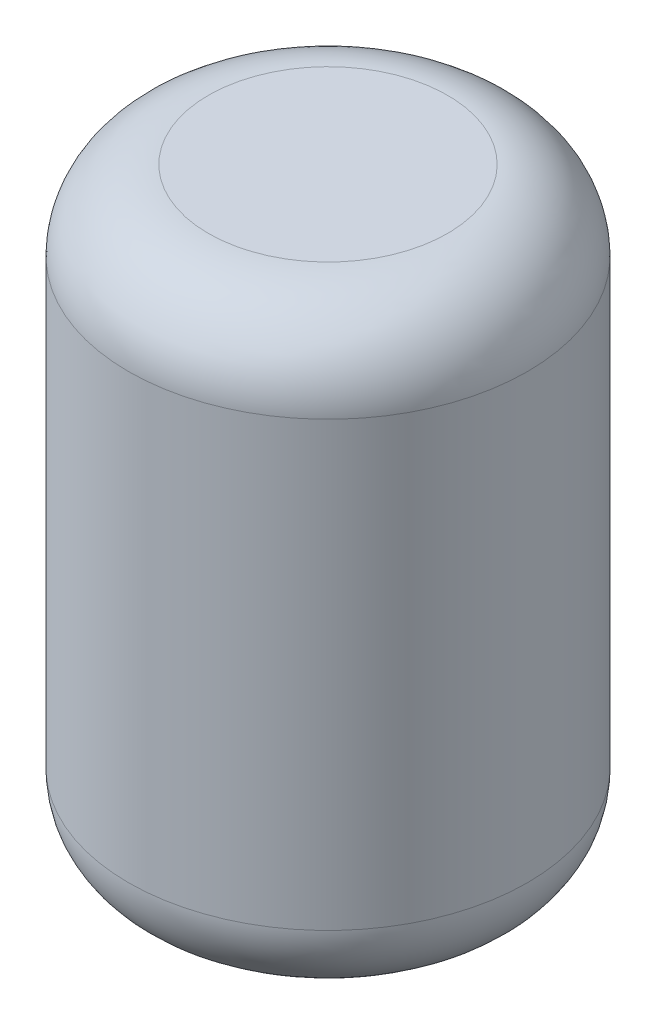
SolidWorks part; units mm, degrees
material "Cast Alloy Steel"
ref_plane "Front Plane" through (0, 0, 0) normal (0, 0, 1) x (1, 0, 0)
ref_plane "Top Plane" through (0, 0, 0) normal (0, 1, 0) x (1, 0, 0)
ref_plane "Right Plane" through (0, 0, 0) normal (1, 0, 0) x (0, 0, -1)
sketch "Sketch1" plane through (0, 0, 0) normal (0, 1, 0) x (1, 0, 0)
  circle A0 centre (0, 0) radius 100
  circle A1 centre (0, 0) radius 98
  dimension "D1" = 200
  dimension "D2" = 2
extrude "Boss-Extrude1" add sketch "Sketch1" along normal blind 300
sketch "Sketch2" plane through (0, 0, 0) normal (0, -1, 0) x (1, 0, 0)
  circle A0 centre (0, 0) radius 100
extrude "Boss-Extrude2" add sketch "Sketch2" against normal blind 2
sketch "Sketch4" plane through (0, 300, 0) normal (0, 1, 0) x (1, 0, 0)
  circle A0 centre (0, 0) radius 100
extrude "Boss-Extrude3" add sketch "Sketch4" along normal blind 2
fillet "Fillet1" radius 40 4 edges at (0, 302, 100) (0, 2, -98) (0, 300, 98) (0, 0, 100)
